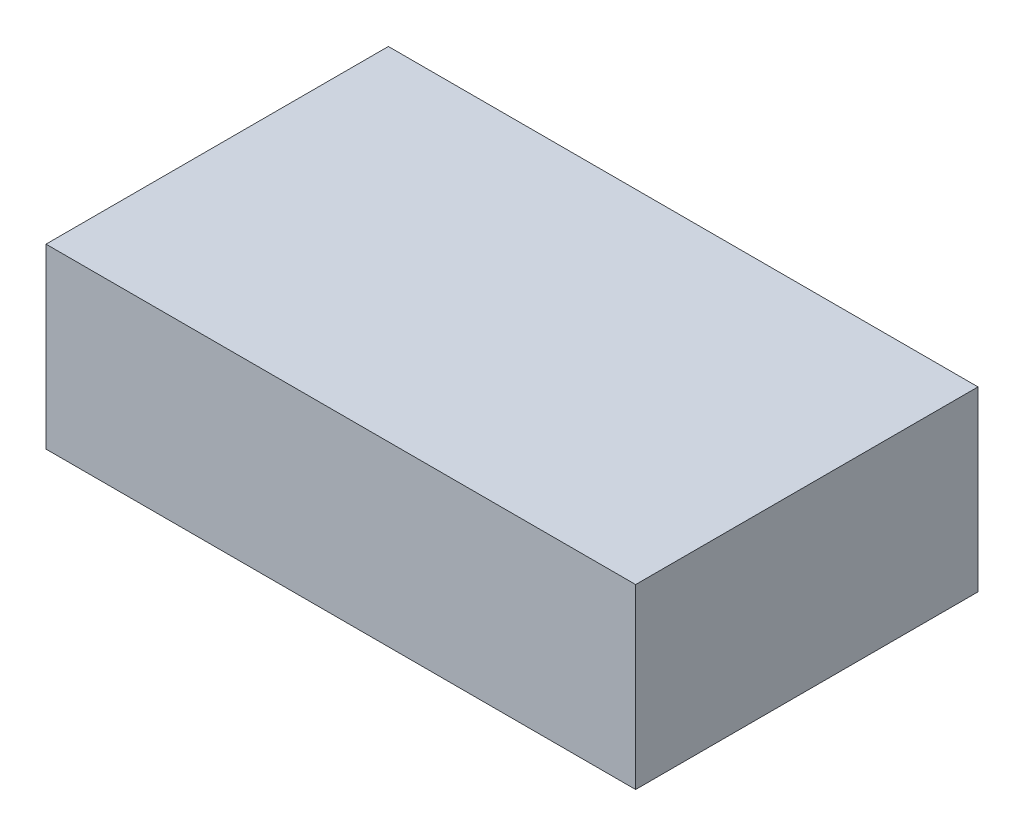
SolidWorks part; units mm, degrees
ref_plane "Front Plane" through (0, 0, 0) normal (0, 0, 1) x (1, 0, 0)
ref_plane "Top Plane" through (0, 0, 0) normal (0, 1, 0) x (1, 0, 0)
ref_plane "Right Plane" through (0, 0, 0) normal (1, 0, 0) x (0, 0, -1)
sketch "Sketch1" plane through (0, 0, 0) normal (0, 1, 0) x (1, 0, 0)
  line L1 (0, 0) -> (46.5, 0)
  line L2 (0, 0) -> (0, 27)
  line L3 (0, 27) -> (46.5, 27)
  line L4 (46.5, 0) -> (46.5, 27)
  dimension "D1" = 46.5
  dimension "D2" = 27
extrude "Boss-Extrude1" add sketch "Sketch1" along normal blind 14
